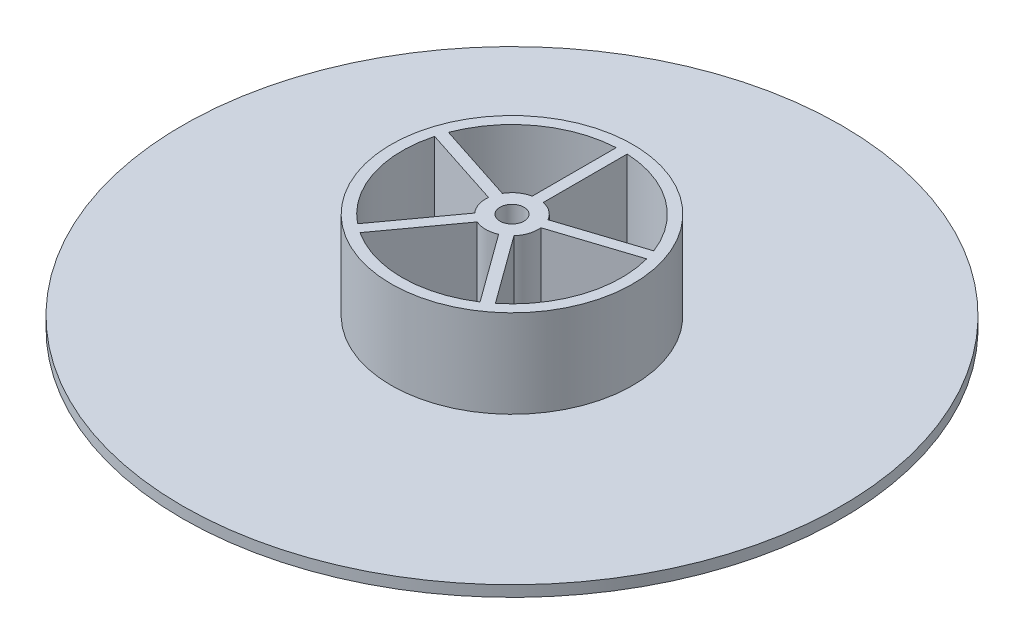
SolidWorks part; units mm, degrees
ref_plane "Front Plane" through (0, 0, 0) normal (0, 0, 1) x (1, 0, 0)
ref_plane "Top Plane" through (0, 0, 0) normal (0, 1, 0) x (1, 0, 0)
ref_plane "Right Plane" through (0, 0, 0) normal (1, 0, 0) x (0, 0, -1)
sketch "Sketch1" plane through (0, 0, 0) normal (0, 1, 0) x (1, 0, 0)
  line L0 (14, 8.0829) -> (48.5692, -11.8756) construction
  line L1 (-14, 0) -> (14, 0) construction
  line L2 (-14, 0) -> (-14, 48) construction
  line L3 (0, 0) -> (-7, -12.1244) construction
  line L4 (14, 0) -> (14, 48) construction
  line L5 (-7, -12.1244) -> (34.5692, -36.1244) construction
  line L6 (7, -12.1244) -> (-34.5692, -36.1244) construction
  line L7 (7, -12.1244) -> (0, 0) construction
  line L8 (-14, 8.0829) -> (-48.5692, -11.8756) construction
  line L9 (14, 48) -> (48.5692, -11.8756) construction
  line L10 (-14, 48) -> (-48.5692, -11.8756) construction
  line L11 (-34.5692, -36.1244) -> (34.5692, -36.1244) construction
  arc A0 (-48.5692, -11.8756) -> (-34.5692, -36.1244) centre (0, 0) ccw construction
  arc A1 (14, 48) -> (-14, 48) centre (0, 0) ccw construction
  arc A2 (34.5692, -36.1244) -> (48.5692, -11.8756) centre (0, 0) ccw construction
  circle A5 centre (0, 0) radius 36.1244
  point P17 (0, 0)
  point P23 (0, 0)
  dimension "D1" = 100
  dimension "D2" = 28
  dimension "D3" = 3
extrude "Boss-Extrude1" add sketch "Sketch1" along normal blind 1.5
sketch "Sketch3" plane through (0, 0, 0) normal (0, 1, 0) x (1, 0, 0)
  line L0 (-30.2828, -43.1244) -> (30.3188, -43.1244) construction
  line L1 (-34.1972, -36.1244) -> (35.2481, -36.1244) construction
  circle A0 centre (0, 0) radius 43.1244
  circle A1 centre (0, 0) radius 75
  circle A2 centre (0, 0) radius 36.1244 construction
  dimension "D1" = 150
  dimension "D2" = 7
extrude "Boss-Extrude2" add sketch "Sketch3" along normal blind 1.5 separate body
sketch "Sketch4" plane through (0, 1.5, 0) normal (0, 1, 0) x (1, 0, 0)
  circle A0 centre (0, 0) radius 75
  circle A1 centre (0, 0) radius 75 construction
extrude "Boss-Extrude3" add sketch "Sketch4" along normal blind 1
sketch "Sketch5" plane through (0, 2.5, 0) normal (0, 1, 0) x (1, 0, 0)
  line L0 (-1.25, 5.8683) -> (-1.25, 24.9687)
  line L1 (1.25, 5.8683) -> (1.25, 24.9687)
  line L2 (5.1949, 3.0022) -> (23.3604, 8.9046)
  line L3 (5.9674, 0.6246) -> (24.1329, 6.5269)
  line L4 (4.4606, -4.0129) -> (15.6875, -19.4654)
  line L5 (2.4381, -5.4823) -> (13.665, -20.9349)
  line L6 (-2.4381, -5.4823) -> (-13.665, -20.9349)
  line L7 (-4.4606, -4.0129) -> (-15.6875, -19.4654)
  line L8 (-5.9674, 0.6246) -> (-24.1329, 6.5269)
  line L9 (-5.1949, 3.0022) -> (-23.3604, 8.9046)
  circle A0 centre (0, 0) radius 27.5
  arc A1 (-1.25, 24.9687) -> (-23.3604, 8.9046) centre (0, 0) ccw
  arc A2 (-1.25, 5.8683) -> (-5.1949, 3.0022) centre (0, 0) ccw
  arc A3 (23.3604, 8.9046) -> (1.25, 24.9687) centre (0, 0) ccw
  arc A4 (5.1949, 3.0022) -> (1.25, 5.8683) centre (0, 0) ccw
  arc A5 (-5.9674, 0.6246) -> (-4.4606, -4.0129) centre (0, 0) ccw
  arc A6 (-24.1329, 6.5269) -> (-15.6875, -19.4654) centre (0, 0) ccw
  arc A7 (-13.665, -20.9349) -> (13.665, -20.9349) centre (0, 0) ccw
  arc A8 (15.6875, -19.4654) -> (24.1329, 6.5269) centre (0, 0) ccw
  arc A9 (-2.4381, -5.4823) -> (2.4381, -5.4823) centre (0, 0) ccw
  arc A10 (4.4606, -4.0129) -> (5.9674, 0.6246) centre (0, 0) ccw
  circle A11 centre (0, 0) radius 2.75
  point P27 (0, 0)
  dimension "D1" = 55
  dimension "D2" = 50
  dimension "D3" = 12
  dimension "D6" = 5.5
  dimension "D4" = 2.5
  dimension "D5" = 5
extrude "Boss-Extrude4" add sketch "Sketch5" along normal blind 20
sketch "Sketch6" plane through (0, 0, 0) normal (0, -1, 0) x (1, 0, 0)
  line L0 (-4, 2.3094) -> (-4, -2.3094)
  line L1 (-4, -2.3094) -> (0, -4.6188)
  line L2 (0, -4.6188) -> (4, -2.3094)
  line L3 (4, -2.3094) -> (4, 2.3094)
  line L4 (4, 2.3094) -> (0, 4.6188)
  line L5 (0, 4.6188) -> (-4, 2.3094)
  circle A0 centre (0, 0) radius 4.6188 construction
  dimension "D1" = 8
  dimension "D2" = 8
extrude "Cut-Extrude1" cut sketch "Sketch6" against normal blind 4
